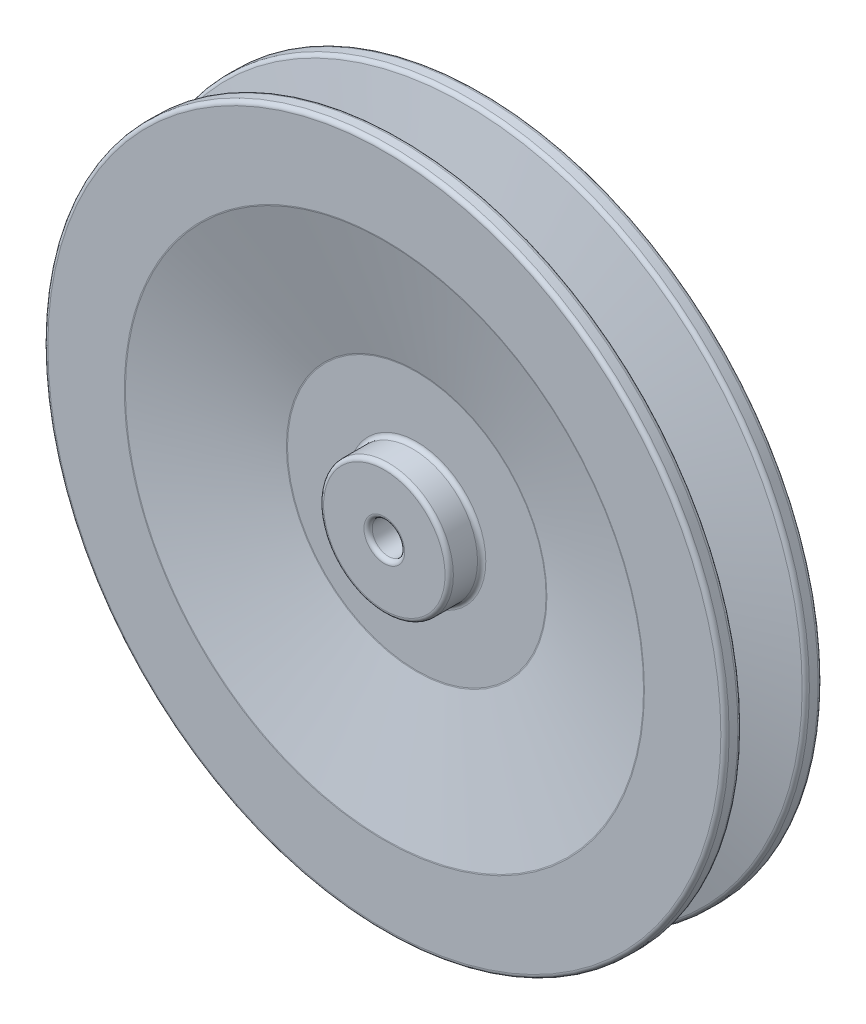
SolidWorks part; units mm, degrees
ref_plane "Front Plane" through (0, 0, 0) normal (0, 0, 1) x (1, 0, 0)
ref_plane "Top Plane" through (0, 0, 0) normal (0, 1, 0) x (1, 0, 0)
ref_plane "Right Plane" through (0, 0, 0) normal (1, 0, 0) x (0, 0, -1)
sketch "Sketch1" plane through (0, 0, 0) normal (0, 1, 0) x (1, 0, 0)
  line L0 (0, 0) -> (0, 19.05) construction
  line L1 (0, 0) -> (3.175, 0) construction
  line L2 (3.175, 0) -> (3.175, 19.05)
  line L3 (0, 0) -> (12.7, 0)
  line L4 (12.7, 0) -> (12.7, 6.35)
  line L5 (12.7, 6.35) -> (25.4, 6.35)
  line L6 (25.4, 6.35) -> (50.8, 0)
  line L7 (50.8, 0) -> (66.675, 0)
  line L8 (66.675, 0) -> (66.675, 3.175)
  line L9 (3.175, 9.525) -> (50.8, 9.525) construction
  line L10 (50.8, 12.1473) -> (50.8, 6.9027)
  line L11 (50.8, 6.9027) -> (66.675, 3.175)
  line L12 (0, 19.05) -> (3.175, 19.05) construction
  line L14 (12.7, 12.7) -> (25.4, 12.7)
  line L15 (12.7, 19.05) -> (12.7, 12.7)
  line L16 (0, 19.05) -> (12.7, 19.05)
  line L17 (50.8, 12.1473) -> (66.675, 15.875)
  line L18 (66.675, 19.05) -> (66.675, 15.875)
  line L19 (50.8, 19.05) -> (66.675, 19.05)
  line L20 (25.4, 12.7) -> (50.8, 19.05)
  point P12 (0, 18.8232)
  dimension "D1" = 9.525
  dimension "D2" = 6.35
  dimension "D3" = 25.4
  dimension "D4" = 12.7
  dimension "D5" = 15.875
  dimension "D6" = 3.175
  dimension "D7" = 19.05
  dimension "D8" = 6.35
  dimension "D9" = 101.6
  dimension "D10" = 16.3068
revolve "Revolve8" add sketch "Sketch1" angle 360 about L0
fillet "Fillet3" radius 0.8128 16 edges at (25.4, 0, -12.7) (12.7, 0, -12.7) (12.7, 0, -19.05) (3.175, 0, -19.05) (3.175, 0, 0) (12.7, 0, 0) (12.7, 0, -6.35) (25.4, 0, -6.35) (50.8, 0, 0) (66.675, 0, 0) (66.675, 0, -3.175) (50.8, 0, -6.9027) (50.8, 0, -12.1473) (66.675, 0, -15.875) (66.675, 0, -19.05) (50.8, 0, -19.05)
